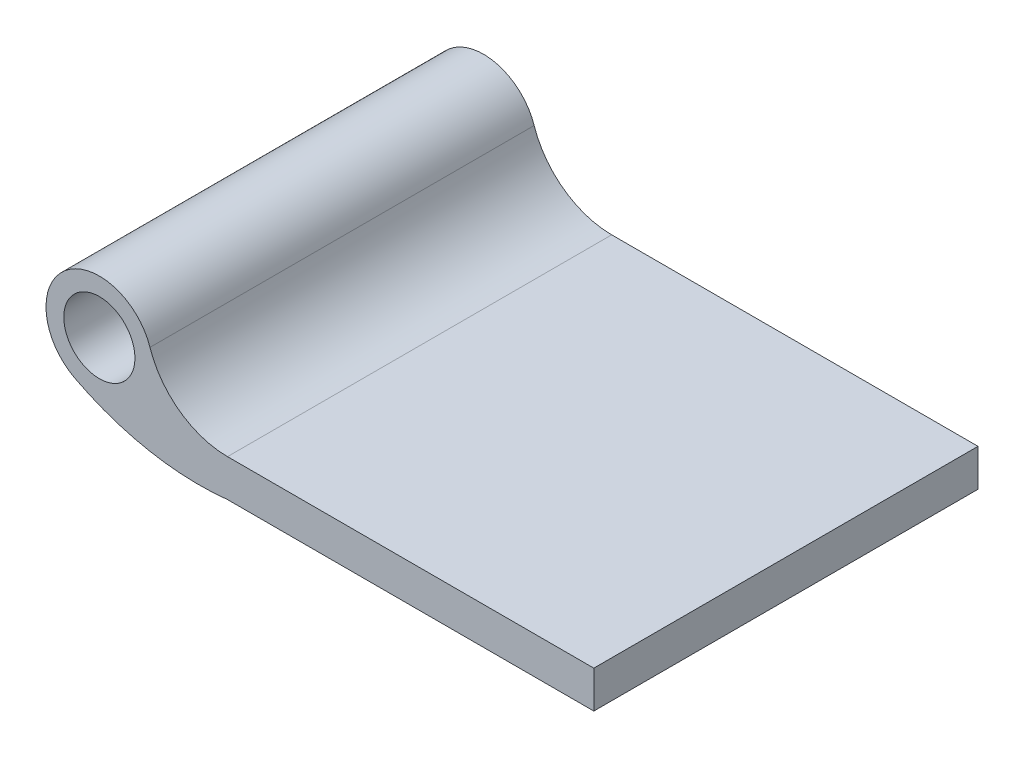
SolidWorks part; units mm, degrees
material "1023 Carbon Steel Sheet (SS)"
ref_plane "Front Plane" through (0, 0, 0) normal (0, 0, 1) x (1, 0, 0)
ref_plane "Top Plane" through (0, 0, 0) normal (0, 1, 0) x (1, 0, 0)
ref_plane "Right Plane" through (0, 0, 0) normal (1, 0, 0) x (0, 0, -1)
sketch "Sketch1" plane through (0, 0, 0) normal (0, 0, 1) x (1, 0, 0)
  line L4 (15, 28.3476) -> (15, -45.7299) construction
  line L5 (0, 28.3476) -> (0, -39.1032) construction
  line L6 (36.0263, -21.4208) -> (36.0263, -10.9628)
  line L7 (139, -10.9628) -> (36.0263, -10.9628)
  line L8 (139, -21.4208) -> (139, -10.9628)
  line L9 (139, -21.4208) -> (36.0263, -21.4208)
  circle A0 centre (0, 0) radius 10
  circle A1 centre (0, 0) radius 15
  arc A4 (14.2296, 4.7452) -> (36.0263, -10.9628) centre (36.0263, 12.0139) ccw
  arc A5 (-6.9149, -13.3111) -> (36.0263, -21.4208) centre (28.023, 53.9438) ccw
  dimension "D1" = 20
  dimension "D2" = 30
extrude "Boss-Extrude1" add sketch "Sketch1" along normal blind 108
